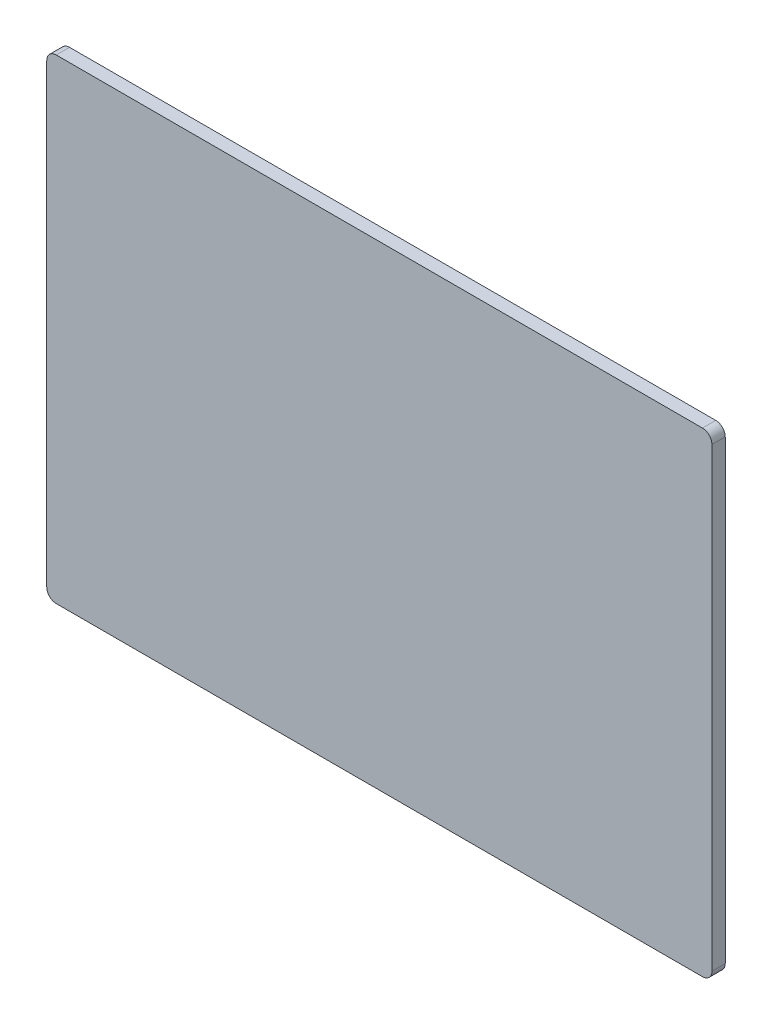
SolidWorks part; units mm, degrees
ref_plane "Plan de face" through (0, 0, 0) normal (0, 0, 1) x (1, 0, 0)
ref_plane "Plan de dessus" through (0, 0, 0) normal (0, 1, 0) x (1, 0, 0)
ref_plane "Plan de droite" through (0, 0, 0) normal (1, 0, 0) x (0, 0, -1)
sketch "Esquisse1" plane through (0, 0, 0) normal (0, 0, 1) x (1, 0, 0)
  line L1 (175, -125) -> (-175, -125)
  line L2 (175, -125) -> (175, 125)
  line L3 (175, 125) -> (-175, 125)
  line L4 (-175, -125) -> (-175, 125)
  line L5 (175, -125) -> (-175, 125) construction
  line L6 (175, 125) -> (-175, -125) construction
  point P0 (0, 0)
  dimension "D1" = 350
  dimension "D2" = 250
extrude "Boss.-Extru.1" add sketch "Esquisse1" along normal blind 7
fillet "Congé1" radius 5 4 edges at (175, -125, 3.5) (-175, -125, 3.5) (-175, 125, 3.5) (175, 125, 3.5)
